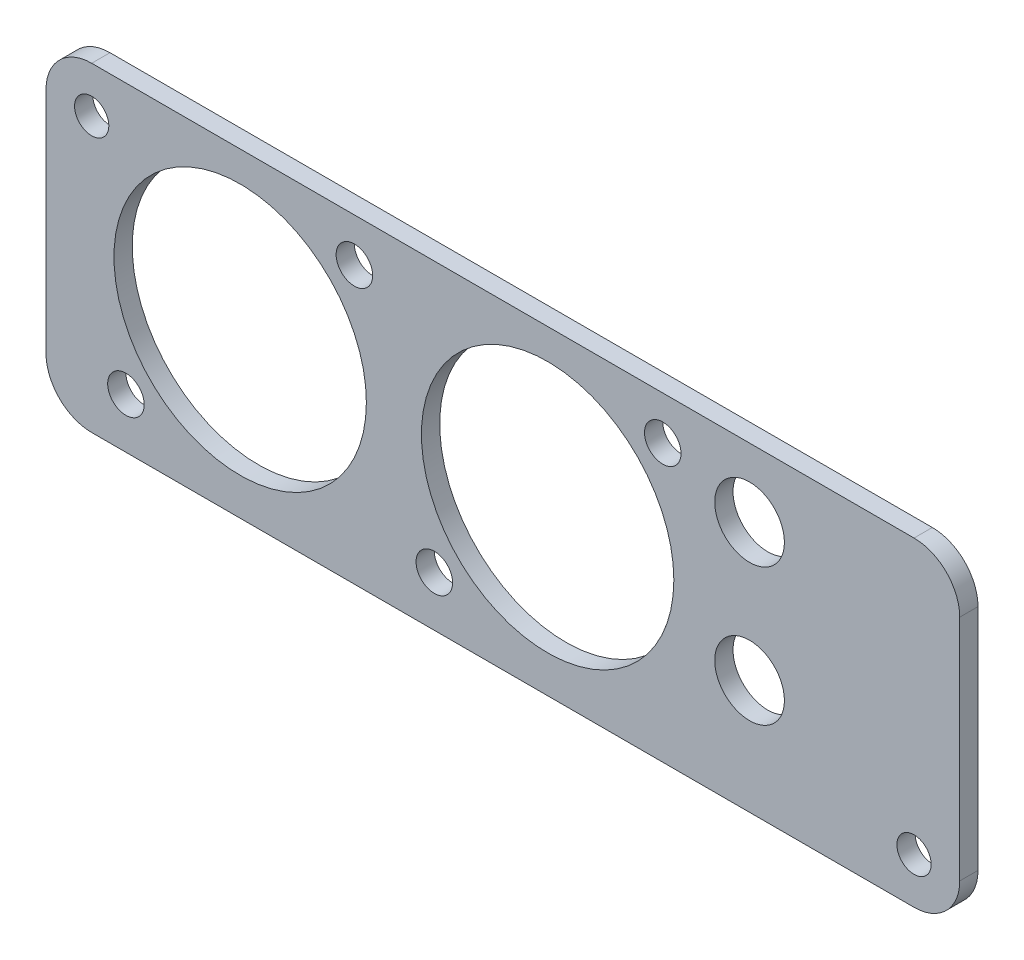
SolidWorks part; units mm, degrees
ref_plane "Front Plane" through (0, 0, 0) normal (0, 0, 1) x (1, 0, 0)
ref_plane "Top Plane" through (0, 0, 0) normal (0, 1, 0) x (1, 0, 0)
ref_plane "Right Plane" through (0, 0, 0) normal (1, 0, 0) x (0, 0, -1)
sketch "Sketch1" plane through (0, 0, 0) normal (0, 0, 1) x (1, 0, 0)
  line L0 (21.6, 8) -> (21.6, -4) construction
  line L1 (-36, -14) -> (36, -14)
  line L2 (-40, -10) -> (-40, 10)
  line L3 (-36, 14) -> (36, 14)
  line L4 (40, -10) -> (40, 10)
  line L5 (-40, -14) -> (40, 14) construction
  line L6 (-40, 14) -> (40, -14) construction
  line L7 (-23, 0.3) -> (3.92, 0.3) construction
  line L8 (-13, 10.2) -> (14, 10.2) construction
  line L9 (-6, -9.6) -> (-33, -9.6) construction
  circle A0 centre (-23, 0.3) radius 11.05
  circle A1 centre (3.92, 0.3) radius 11.05
  circle A2 centre (14, 10.2) radius 1.6
  circle A3 centre (-6, -9.6) radius 1.6
  circle A4 centre (-33, -9.6) radius 1.6
  circle A5 centre (-13, 10.2) radius 1.6
  circle A6 centre (-36, 10) radius 1.5
  circle A7 centre (21.6, 8) radius 3.05
  circle A8 centre (21.6, -4) radius 3.05
  circle A9 centre (36, -10) radius 1.5
  arc A10 (-36, -14) -> (-40, -10) centre (-36, -10) cw
  arc A11 (36, -14) -> (40, -10) centre (36, -10) ccw
  arc A12 (36, 14) -> (40, 10) centre (36, 10) cw
  arc A13 (-40, 10) -> (-36, 14) centre (-36, 10) cw
  point P0 (0, 0)
  dimension "D10" = 54
  dimension "D16" = 3
  dimension "D17" = 3
  dimension "D18" = 22.1
  dimension "D19" = 13.7
  dimension "D20" = 3.2
  dimension "D21" = 6.1
  dimension "D22" = 3.8
  dimension "D24" = 4
  dimension "D1" = 80
  dimension "D2" = 28
  dimension "D3" = 17
  dimension "D4" = 43.92
  dimension "D5" = 61.6
  dimension "D6" = 76
  dimension "D7" = 7
  dimension "D8" = 34
  dimension "D9" = 27
  dimension "D11" = 24
  dimension "D12" = 18
  dimension "D13" = 6
  dimension "D14" = 4
  dimension "D15" = 4
  dimension "D23" = 23.6
extrude "Boss-Extrude1" add sketch "Sketch1" along normal blind 1.6
